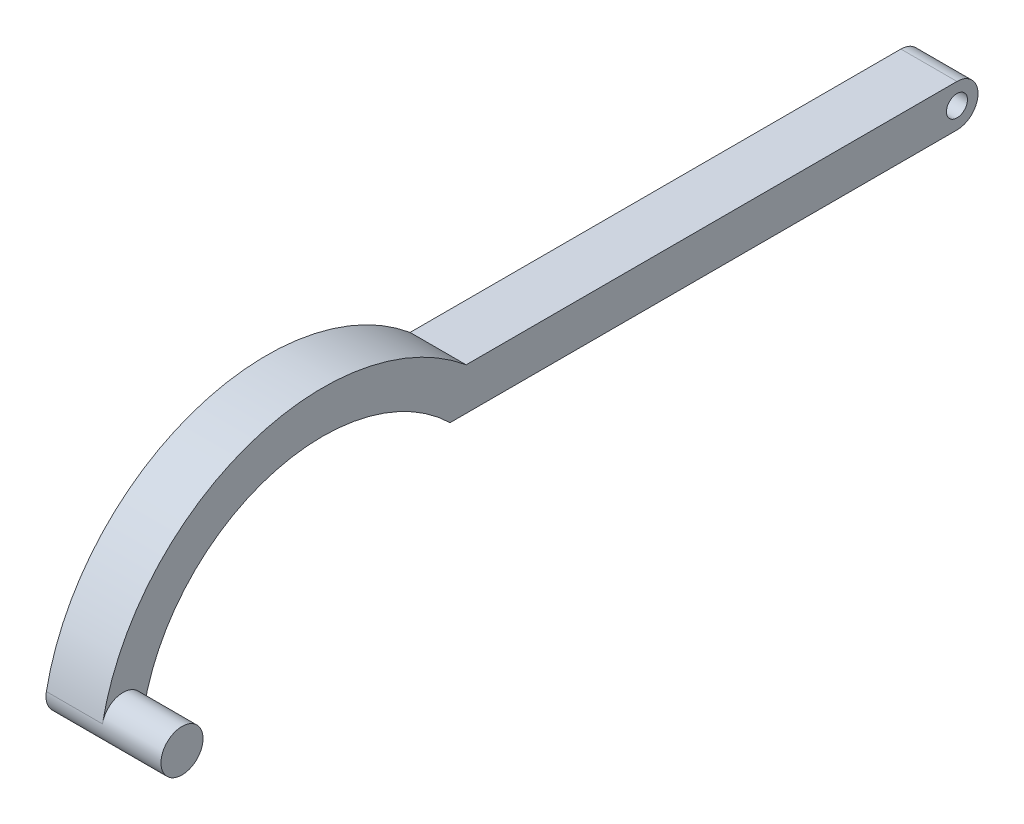
SolidWorks part; units mm, degrees
ref_plane "Front Plane" through (0, 0, 0) normal (0, 0, 1) x (1, 0, 0)
ref_plane "Top Plane" through (0, 0, 0) normal (0, 1, 0) x (1, 0, 0)
ref_plane "Right Plane" through (0, 0, 0) normal (1, 0, 0) x (0, 0, -1)
sketch "Sketch1" plane through (0, 0, 0) normal (1, 0, 0) x (0, 0, -1)
  line L0 (0, 0) -> (59.4643, 8) construction
  line L2 (59.4643, 9.5) -> (24.4643, 9.5)
  line L4 (59.4643, 6.5) -> (23.3144, 6.5)
  arc A0 (-1.4718, 0.2893) -> (1.4718, -0.2893) centre (0, 0) ccw
  arc A1 (59.4643, 6.5) -> (59.4643, 9.5) centre (59.4643, 8) ccw
  circle A4 centre (0, 0) radius 1.5 construction
  circle A5 centre (59.4643, 8) radius 0.75
  arc A6 (1.4718, -0.2893) -> (23.3144, 6.5) centre (14.2277, -2.7969) cw
  arc A7 (24.4643, 9.5) -> (-1.4718, 0.2893) centre (14.2277, -2.7969) ccw
  point P11 (-0.3904, 2.1734)
  point P14 (0.9688, 2.8046)
  point P15 (1.1238, -0.9935)
  point P17 (0, 0)
  point P18 (1.2985, -0.7509)
  point P19 (-1.0444, 1.0767)
  point P20 (-1.3076, 0.735)
  point P21 (-1.3333, 0.6873)
  dimension "D1" = 60
  dimension "D5" = 3
  dimension "D6" = 1.5
  dimension "D9" = 13
  dimension "D10" = 3
  dimension "D3" = 8
  dimension "D7" = 35
extrude "Boss-Extrude1" add sketch "Sketch1" along normal blind 4
sketch "Sketch2" plane through (4, 0, 0) normal (1, 0, 0) x (0, 0, -1)
  circle A0 centre (0, 0) radius 1.5
extrude "Boss-Extrude2" add sketch "Sketch2" along normal blind 4.2
